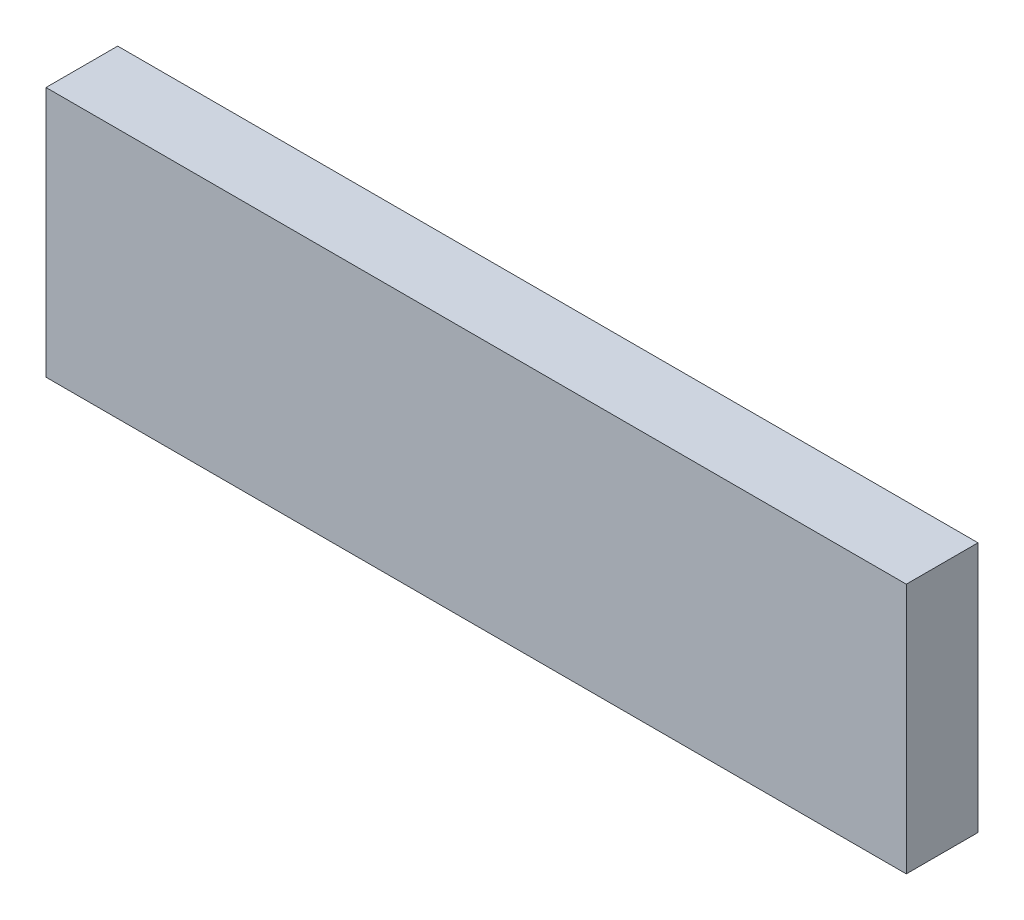
SolidWorks part; units mm, degrees
ref_plane "前视基准面" through (0, 0, 0) normal (0, 0, 1) x (1, 0, 0)
ref_plane "上视基准面" through (0, 0, 0) normal (0, 1, 0) x (1, 0, 0)
ref_plane "右视基准面" through (0, 0, 0) normal (1, 0, 0) x (0, 0, -1)
other "Configuration Table"
sketch "草图1" plane through (0, 0, 0) normal (0, 0, 1) x (1, 0, 0)
  line L1 (-120, -35) -> (120, -35)
  line L2 (-120, -35) -> (-120, 35)
  line L3 (-120, 35) -> (120, 35)
  line L4 (120, -35) -> (120, 35)
  line L5 (-120, -35) -> (120, 35) construction
  line L6 (-120, 35) -> (120, -35) construction
  point P0 (0, 0)
extrude "凸台-拉伸1" add sketch "草图1" along normal blind 20
